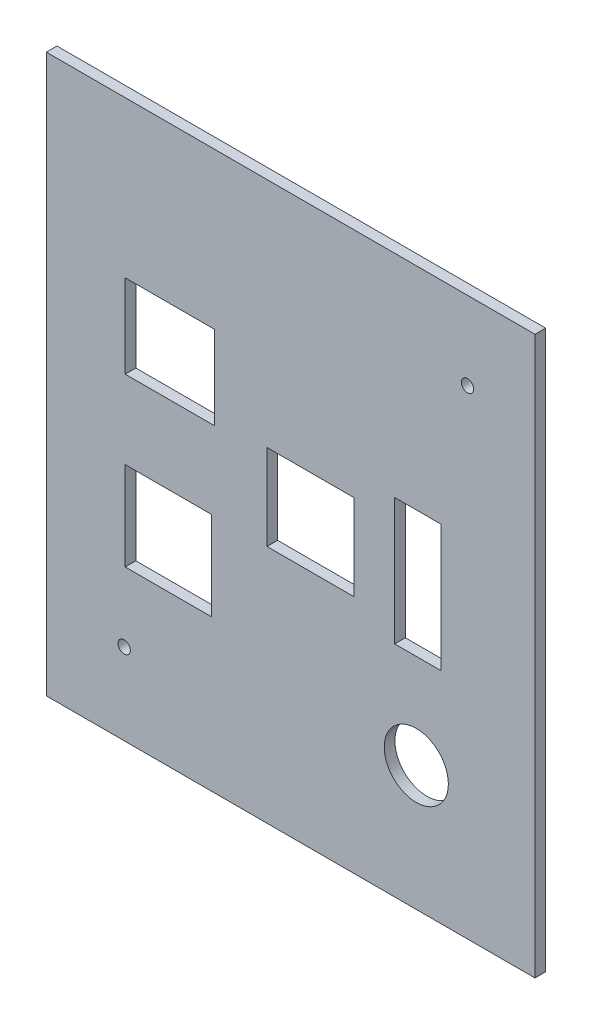
SolidWorks part; units mm, degrees
ref_plane "Front Plane" through (0, 0, 0) normal (0, 0, 1) x (1, 0, 0)
ref_plane "Top Plane" through (0, 0, 0) normal (0, 1, 0) x (1, 0, 0)
ref_plane "Right Plane" through (0, 0, 0) normal (1, 0, 0) x (0, 0, -1)
ref_plane "Plane1" through (0, 0, 8.89) normal (0, 0, 1) x (1, 0, 0)
sketch "Sketch2" plane through (0, 0, 8.89) normal (0, 0, 1) x (1, 0, 0)
  line L0 (47.4311, -19.2747) -> (47.4311, -152.4398)
  line L1 (47.4311, -19.2747) -> (164.1566, -19.2747)
  line L2 (47.4311, -152.4398) -> (164.1566, -152.4398)
  line L3 (164.1566, -19.2747) -> (164.1566, -152.4398)
extrude "Boss-Extrude1" add sketch "Sketch2" along normal blind 2.54
sketch "Sketch3" plane through (0, 0, 11.43) normal (0, 0, 1) x (1, 0, 0)
  line L0 (66.2647, -116.3548) -> (66.2647, -95.185)
  line L1 (66.2647, -116.3548) -> (86.8883, -116.3548)
  line L2 (66.2647, -95.185) -> (86.8883, -95.185)
  line L3 (86.8883, -116.3548) -> (86.8883, -95.185)
  line L4 (100.1365, -95.185) -> (100.1365, -74.698)
  line L5 (100.1365, -95.185) -> (120.8966, -95.185)
  line L6 (100.1365, -74.698) -> (120.8966, -74.698)
  line L7 (120.8966, -95.185) -> (120.8966, -74.698)
  line L8 (66.2647, -76.4736) -> (66.2647, -56.5329)
  line L9 (66.2647, -76.4736) -> (87.5712, -76.4736)
  line L10 (66.2647, -56.5329) -> (87.5712, -56.5329)
  line L11 (87.5712, -76.4736) -> (87.5712, -56.5329)
extrude "Cut-Extrude1" cut sketch "Sketch3" against normal blind 2.54
sketch "Sketch5" plane through (0, 0, 11.43) normal (0, 0, 1) x (1, 0, 0)
  circle A0 centre (135.8, -122.65) radius 7.657
extrude "Cut-Extrude3" cut sketch "Sketch5" against normal blind 2.54
sketch "Sketch7" plane through (0, 0, 11.43) normal (0, 0, 1) x (1, 0, 0)
  line L4 (130.645, -100.0862) -> (141.6535, -100.0862)
  line L5 (130.645, -100.0862) -> (130.645, -69.7893)
  line L6 (141.6535, -100.0862) -> (141.6535, -69.7893)
  line L7 (130.645, -69.7893) -> (141.6535, -69.7893)
extrude "Cut-Extrude4" cut sketch "Sketch7" against normal blind 2.54
sketch "Sketch8" plane through (0, 0, 11.43) normal (0, 0, 1) x (1, 0, 0)
  circle A1 centre (66.0153, -133.0073) radius 1.475
  circle A2 centre (148.0321, -37.9645) radius 1.475
extrude "Cut-Extrude6" cut sketch "Sketch8" against normal blind 2.95
